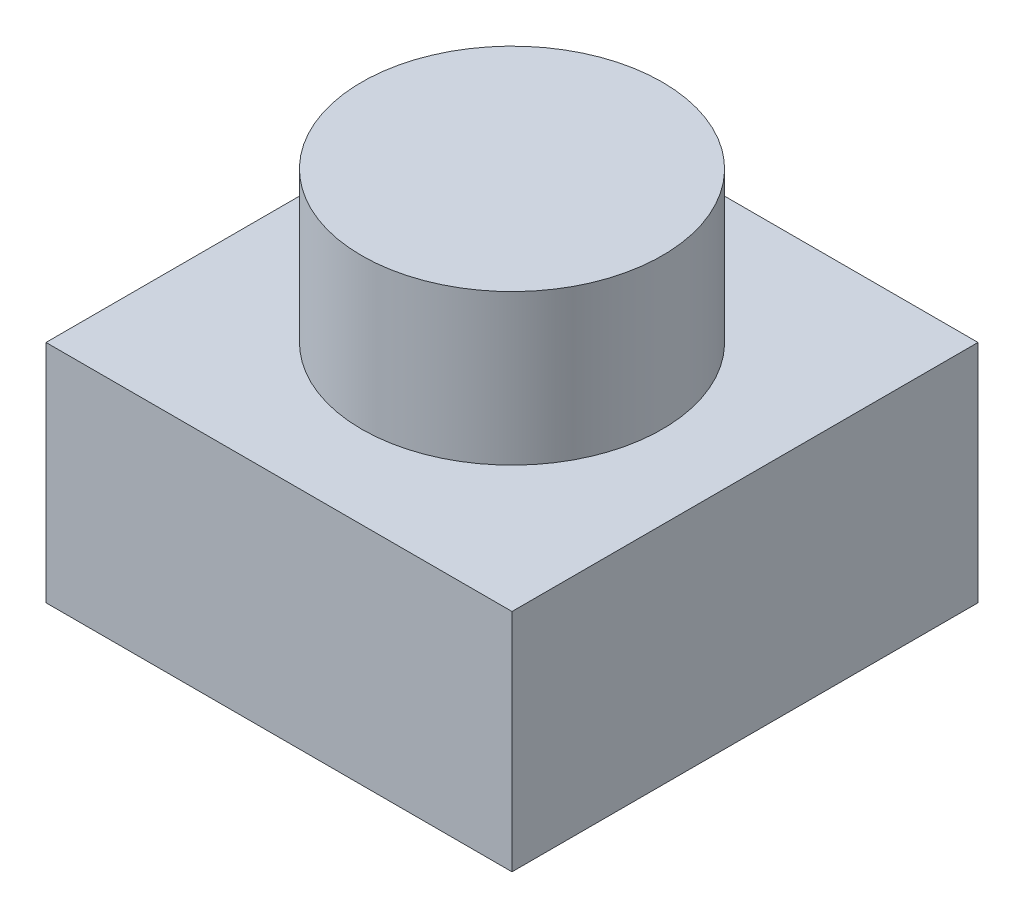
SolidWorks part; units mm, degrees
ref_plane "Front Plane" through (0, 0, 0) normal (0, 0, 1) x (1, 0, 0)
ref_plane "Top Plane" through (0, 0, 0) normal (0, 1, 0) x (1, 0, 0)
ref_plane "Right Plane" through (0, 0, 0) normal (1, 0, 0) x (0, 0, -1)
sketch "Sketch1" plane through (0, 0, 0) normal (0, 1, 0) x (1, 0, 0)
  line L1 (-3.1, -3.1) -> (3.1, -3.1)
  line L2 (-3.1, -3.1) -> (-3.1, 3.1)
  line L3 (-3.1, 3.1) -> (3.1, 3.1)
  line L4 (3.1, -3.1) -> (3.1, 3.1)
  line L5 (-3.1, -3.1) -> (3.1, 3.1) construction
  line L6 (-3.1, 3.1) -> (3.1, -3.1) construction
  point P0 (0, 0)
  dimension "D1" = 6.2
  dimension "D2" = 6.2
extrude "Boss-Extrude1" add sketch "Sketch1" along normal blind 3
sketch "Sketch2" plane through (0, 3, 0) normal (0, 1, 0) x (1, 0, 0)
  circle A0 centre (0, 0) radius 2
  dimension "D1" = 4
extrude "Boss-Extrude2" add sketch "Sketch2" along normal blind 2
